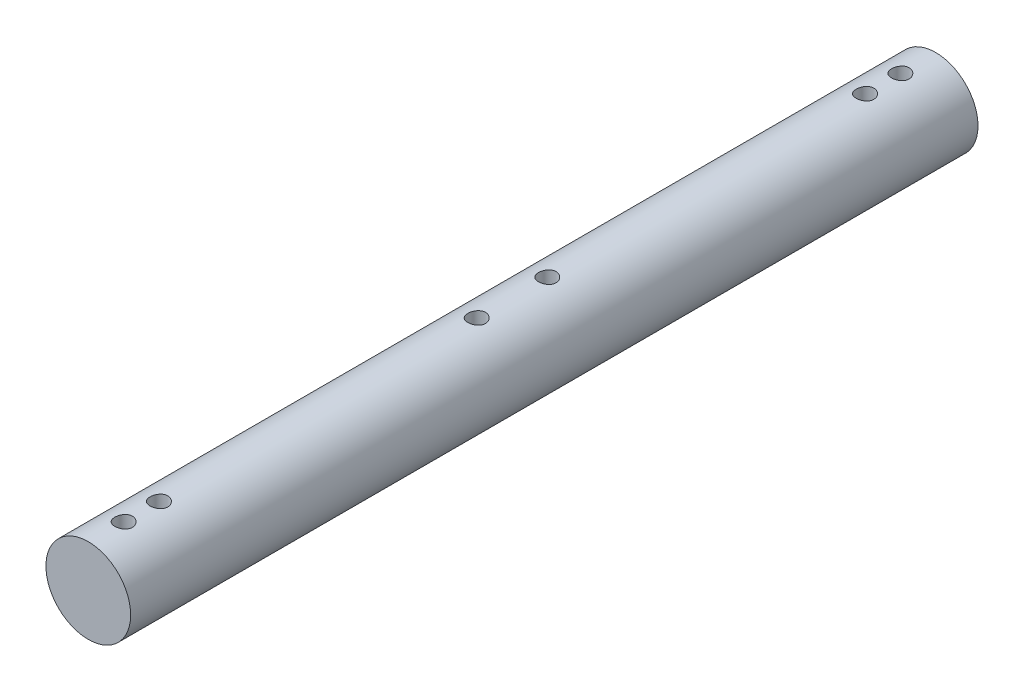
SolidWorks part; units mm, degrees
ref_plane "Front Plane" through (0, 0, 0) normal (0, 0, 1) x (1, 0, 0)
ref_plane "Top Plane" through (0, 0, 0) normal (0, 1, 0) x (1, 0, 0)
ref_plane "Right Plane" through (0, 0, 0) normal (1, 0, 0) x (0, 0, -1)
sketch "Sketch1" plane through (0, 0, 0) normal (0, 0, 1) x (1, 0, 0)
  circle A0 centre (0, 0) radius 6
  dimension "D1" = 12
extrude "Boss-Extrude1" add sketch "Sketch1" along normal blind 120
sketch "Sketch12" plane through (0, 0, 0) normal (0, 1, 0) x (1, 0, 0)
  line L0 (0, 0) -> (0, -120) construction
  line L1 (-6, -120) -> (6, -120) construction
  line L2 (6, -60) -> (-6, -60) construction
  line L3 (-6, 0) -> (-6, -120) construction
  circle A0 centre (0, -5) radius 1.25
  circle A1 centre (0, -10) radius 1.25
  circle A2 centre (0, -65) radius 1.25
  circle A3 centre (0, -55) radius 1.25
  circle A4 centre (0, -110) radius 1.25
  circle A5 centre (0, -115) radius 1.25
  point P11 (0, 0)
  point P16 (0, -60)
  dimension "D1" = 2.5
  dimension "D2" = 5
  dimension "D3" = 10
  dimension "D4" = 65
extrude "Cut-Extrude2" cut sketch "Sketch12" against normal through all and the other way through all
